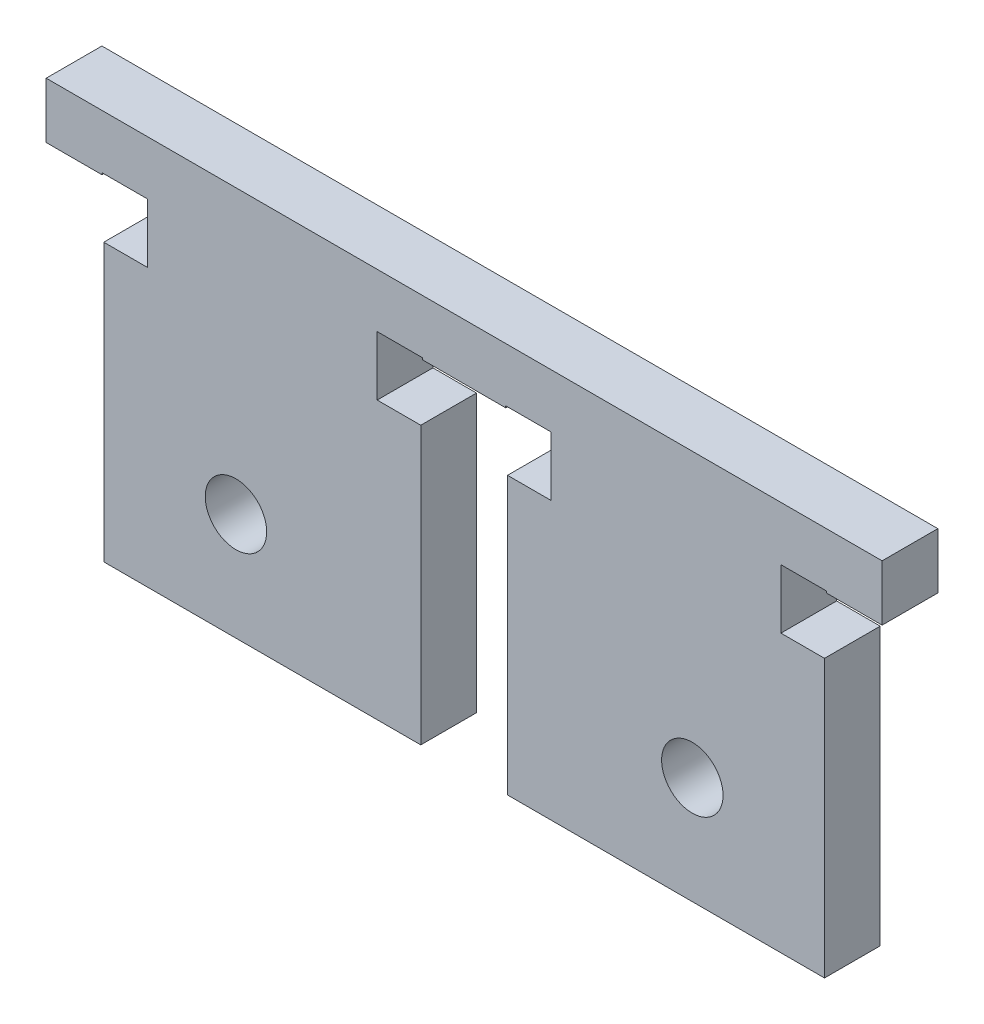
SolidWorks part; units mm, degrees
material "AISI 4130 Steel, annealed at 865C"
ref_plane "X-Y Datum" through (0, 0, 0) normal (0, 0, 1) x (1, 0, 0)
ref_plane "X-Z Datum" through (0, 0, 0) normal (0, 1, 0) x (1, 0, 0)
ref_plane "Y-Z Datum" through (0, 0, 0) normal (1, 0, 0) x (0, 0, -1)
sketch "Sketch3" plane through (0, 0, 0) normal (0, 0, 1) x (1, 0, 0)
  line L1 (-47.625, -30.48) -> (47.625, -30.48)
  line L2 (-47.625, -30.48) -> (-47.625, 30.48)
  line L3 (-47.625, 30.48) -> (47.625, 30.48)
  line L4 (47.625, -30.48) -> (47.625, 30.48)
  line L5 (-47.625, -30.48) -> (47.625, 30.48) construction
  line L6 (-47.625, 30.48) -> (47.625, -30.48) construction
  point P0 (0, 0)
  dimension "D1" = 95.25
  dimension "D2" = 60.96
extrude "Boss-Extrude1" add sketch "Sketch3" along normal blind 6.35
sketch "Sketch4" plane through (0, 0, 6.35) normal (0, 0, 1) x (1, 0, 0)
  line L0 (-47.625, 15.24) -> (-41.0616, 15.24)
  line L1 (-47.625, 30.48) -> (-47.625, -30.48) construction
  line L2 (-41.0616, 15.24) -> (-4.5491, 15.24)
  line L3 (-4.5491, 15.24) -> (4.5491, 15.24)
  line L4 (4.5491, 15.24) -> (41.0616, 15.24)
  line L5 (41.0616, 15.24) -> (47.625, 15.24)
  line L6 (47.625, -30.48) -> (47.625, 30.48) construction
  line L7 (0, 15.24) -> (0, -30.48) construction
  line L8 (-41.0616, 15.24) -> (-47.625, 15.24)
  line L9 (-41.0616, 15.24) -> (-41.0616, -30.48)
  line L10 (-41.0616, -30.48) -> (-47.625, -30.48)
  line L11 (-47.625, 15.24) -> (-47.625, -30.48)
  line L12 (-47.625, -30.48) -> (47.625, -30.48) construction
  line L13 (-1.5875, -16.0071) -> (1.5875, -16.0071)
  line L14 (-1.5875, -16.0071) -> (-1.5875, 0.7671)
  line L17 (-4.5491, 15.24) -> (4.5491, 15.24)
  line L19 (-4.9418, -30.48) -> (4.9418, -30.48)
  line L20 (-4.9418, -30.48) -> (-4.9418, 15.24)
  line L25 (-4.9418, 15.24) -> (4.9418, 15.24)
  line L26 (4.9418, -30.48) -> (4.9418, 15.24)
  line L27 (41.0616, 15.24) -> (47.625, 15.24)
  line L28 (41.0616, 15.24) -> (41.0616, -30.48)
  line L29 (41.0616, -30.48) -> (47.625, -30.48)
  line L31 (-4.9418, -30.48) -> (4.9418, 15.24) construction
  line L32 (-4.9418, 15.24) -> (4.9418, -30.48) construction
  line L33 (-1.5875, 0.7671) -> (1.5875, 0.7671)
  line L34 (1.5875, -16.0071) -> (1.5875, 0.7671)
  line L35 (-1.5875, -16.0071) -> (1.5875, 0.7671) construction
  line L36 (-1.5875, 0.7671) -> (1.5875, -16.0071) construction
  point P15 (0, -7.62)
  point P20 (0, -7.62)
  dimension "D1" = 6.5634
  dimension "D2" = 36.5125
  dimension "D3" = 6.5634
  dimension "D4" = 36.5125
  dimension "D5" = 9.8837
  dimension "D6" = 45.72
  dimension "D7" = 3.175
  dimension "D9" = 45.72
extrude "Cut-Extrude1" cut sketch "Sketch4" against normal blind 6.35
sketch "Sketch5" plane through (0, 0, 6.35) normal (0, 0, 1) x (1, 0, 0)
  line L0 (-41.2648, 15.4432) -> (-36.0959, 15.4432)
  line L9 (-41.0616, 15.24) -> (-4.9418, 15.24)
  line L14 (-36.0959, 15.4432) -> (-36.0959, 8.6868)
  line L15 (-41.2648, 8.6868) -> (-36.0959, 8.6868)
  line L24 (-41.2648, 15.4432) -> (-41.2648, 8.6868)
  line L25 (-4.7386, 15.4432) -> (-4.7386, 8.6868)
  line L26 (-41.0616, 15.24) -> (-36.2991, 15.24)
  line L27 (-41.0616, 15.24) -> (-41.0616, 8.89)
  line L28 (-41.0616, 8.89) -> (-36.2991, 8.89)
  line L29 (-36.2991, 15.24) -> (-36.2991, 8.89)
  line L30 (-4.9418, 15.24) -> (-9.7043, 15.24)
  line L31 (-4.9418, 15.24) -> (-4.9418, 8.89)
  line L32 (-4.9418, 8.89) -> (-9.7043, 8.89)
  line L33 (-9.7043, 15.24) -> (-9.7043, 8.89)
  line L34 (-4.7386, 8.6868) -> (-9.9075, 8.6868)
  line L35 (-9.9075, 15.4432) -> (-9.9075, 8.6868)
  line L36 (-4.7386, 15.4432) -> (-9.9075, 15.4432)
  dimension "D1" = 6.35
  dimension "D2" = 4.7625
  dimension "D3" = 4.7625
  dimension "D4" = 0.2032
  dimension "D5" = 0.2032
extrude "Cut-Extrude2" cut sketch "Sketch5" against normal through all
mirror "Mirror1" about plane through (0, 0, 0) normal (1, 0, 0) of "Cut-Extrude2"
sketch "Sketch8" [suppressed] plane through (0, 15.24, 0) normal (0, -1, 0) x (1, 0, 0)
  line L0 (-9.525, 3.175) -> (9.525, 3.175) construction
  line L1 (-9.525, 0) -> (-9.525, 6.35) construction
  line L2 (9.525, 0) -> (9.525, 6.35) construction
  line L3 (-4.7625, 6.35) -> (4.7625, 6.35) construction
  line L4 (-4.7625, 0) -> (4.7625, 0)
  line L5 (-4.7625, 0) -> (-4.7625, 6.35)
  line L6 (-4.7625, 6.35) -> (4.7625, 6.35)
  line L7 (4.7625, 0) -> (4.7625, 6.35)
  line L8 (-4.7625, 0) -> (4.7625, 6.35) construction
  line L9 (-4.7625, 6.35) -> (4.7625, 0) construction
  point P6 (0, 3.175)
  line M3 (-4.7625, 0) -> (4.7625, 0)
  dimension "D1" = 4.7625
extrude "Cut-Extrude3" [suppressed] cut sketch "Sketch8" against normal blind 1.5875 contours L7 L0 L5 M3
sketch "Sketch9" plane through (0, 30.48, 0) normal (0, 1, 0) x (1, 0, 0)
  line L1 (-47.625, 0) -> (47.625, 0)
  line L2 (-47.625, 0) -> (-47.625, -6.35)
  line L3 (-47.625, -6.35) -> (47.625, -6.35)
  line L4 (47.625, 0) -> (47.625, -6.35)
extrude "Cut-Extrude6" cut sketch "Sketch9" against normal blind 8.89
sketch "Sketch10" plane through (0, 0, 6.35) normal (0, 0, 1) x (1, 0, 0)
  line L0 (0, 0) -> (0, -30.2463) construction
  line L1 (-26, -10.6279) -> (26, -10.6279) construction
  circle A1 centre (-26, -10.6279) radius 3.3015
  circle A3 centre (26, -10.6279) radius 3.3015
  point P2 (26, -10.6279)
  point P10 (-26, -10.6279)
  point P21 (-26, -10.6279)
  point P23 (26, -10.6279)
  dimension "D2" = 6.603
  dimension "D1" = 52
sketch "Sketch11" plane through (0, -30.48, 0) normal (0, -1, 0) x (1, 0, 0)
  line L1 (-41.0616, 6.35) -> (41.0616, 6.35)
  line L2 (-41.0616, 6.35) -> (-41.0616, 0)
  line L3 (-41.0616, 0) -> (41.0616, 0)
  line L4 (41.0616, 6.35) -> (41.0616, 0)
extrude "Cut-Extrude9" cut sketch "Sketch11" against normal blind 7.62
hole_wizard "M6 Clearance Hole2" positions "Sketch10" profile "Sketch12" hole size "M6" standard "ANSI Metric" end condition through all
sketch "Sketch12" plane through (26, -10.6279, 6.35) normal (1, 0, 0) x (0, -1, 0)
  line L0 (0, 0) -> (0, 6.35)
  line L1 (0, 6.35) -> (3.5, 6.35)
  line L2 (3.5, 6.35) -> (3.5, 0)
  line L5 (3.5, 0) -> (0, 0)
  line L11 (0, -6.35) -> (0, 107.95) construction
  dimension "Thru Hole Dia." = 7
  dimension "Thru Hole Depth" = 6.35
